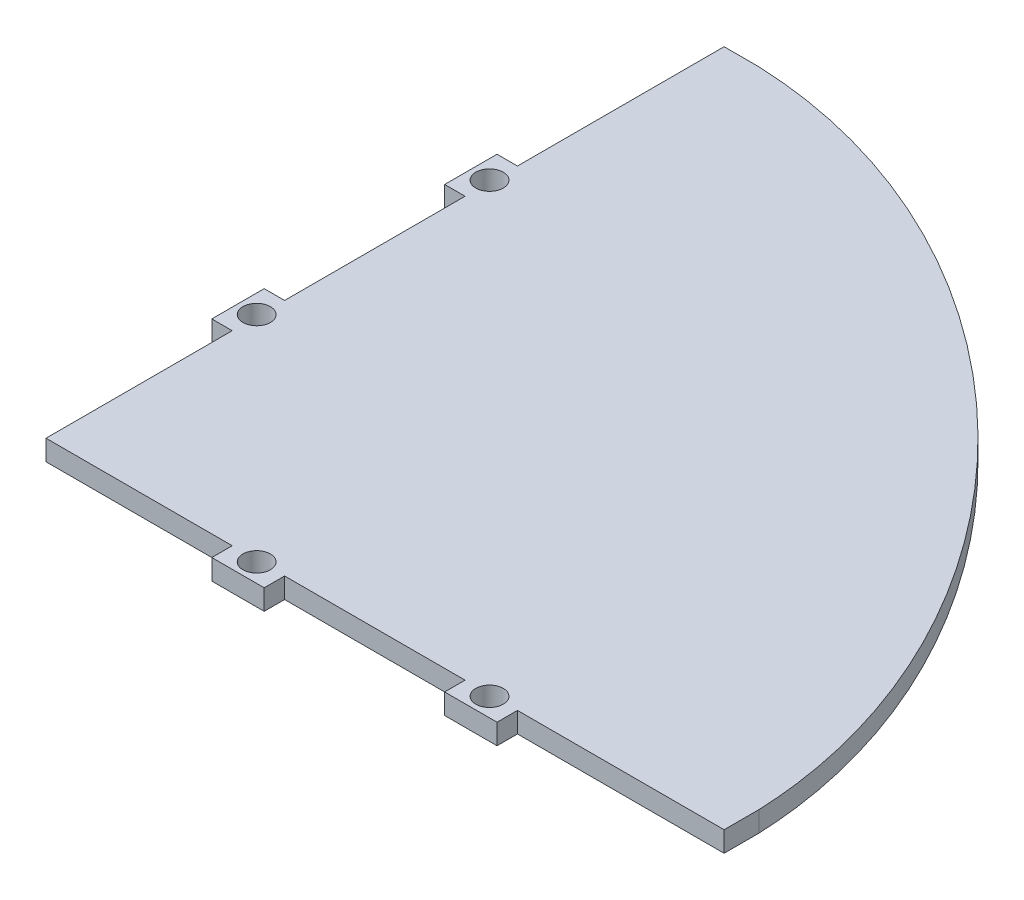
SolidWorks part; units mm, degrees
ref_plane "前视基准面" through (0, 0, 0) normal (0, 0, 1) x (1, 0, 0)
ref_plane "上视基准面" through (0, 0, 0) normal (0, 1, 0) x (1, 0, 0)
ref_plane "右视基准面" through (0, 0, 0) normal (1, 0, 0) x (0, 0, -1)
sketch "草图1" plane through (0, 0, 0) normal (0, 1, 0) x (1, 0, 0)
  line L0 (0, 34.7049) -> (-2.9718, 34.7049)
  line L1 (0, 0) -> (98.6282, 0)
  line L2 (0, 0) -> (0, 98.6282)
  line L3 (0, 98.6282) -> (98.6282, 98.6282)
  line L4 (98.6282, 0) -> (98.6282, 98.6282)
  line L5 (-2.9718, 34.7049) -> (-2.9718, 27.0849)
  line L6 (-2.9718, 27.0849) -> (0, 27.0849)
  line L7 (0, 68.5715) -> (-2.9718, 68.5715)
  line L8 (-2.9718, 68.5715) -> (-2.9718, 60.9515)
  line L9 (-2.9718, 60.9515) -> (0, 60.9515)
  line L10 (0, 0) -> (98.6282, 98.6282) construction
  line L11 (-0.254, 68.5715) -> (-0.254, 60.9515) construction
  line L12 (-0.254, 34.7049) -> (-0.254, 27.0849) construction
  line L13 (27.0849, -2.9718) -> (27.0849, 0)
  line L14 (34.7049, -2.9718) -> (27.0849, -2.9718)
  line L15 (34.7049, 0) -> (34.7049, -2.9718)
  line L16 (60.9515, -2.9718) -> (60.9515, 0)
  line L17 (68.5715, -2.9718) -> (60.9515, -2.9718)
  line L18 (68.5715, 0) -> (68.5715, -2.9718)
  circle A0 centre (-0.254, 64.7615) radius 2
  circle A1 centre (-0.254, 30.8949) radius 2
  circle A2 centre (30.8949, -0.254) radius 2
  circle A3 centre (64.7615, -0.254) radius 2
  spline S0 degree 3 poles (0, 98.6282) (47.2986, 100.5712) (100.5712, 47.2986) (98.6282, 0) knots 0 0 0 0 1 1 1 1
  point P21 (-0.254, 64.7615)
  point P24 (-0.254, 30.8949)
  dimension "D3" = 5.08
  dimension "D11" = 4
  dimension "D12" = 4
  dimension "D1" = 98.6282
  dimension "D2" = 98.6282
  dimension "D4" = 5.08
  dimension "D5" = 2.9718
  dimension "D6" = 7.62
  dimension "D7" = 27.0849
  dimension "D8" = 2.9718
  dimension "D9" = 7.62
  dimension "D10" = 30.0567
  dimension "D13" = 0.254
  dimension "D14" = 0.254
extrude "凸台-拉伸1" add sketch "草图1" along normal blind 2.9718 contours S0 L3 L2 A0 A1 L1 A2 A3 L4 | A0 L2 L7 L8 L9 | A1 L2 L0 L5 L6 | L1 A2 L13 L14 L15 | L1 A3 L16 L17 L18
